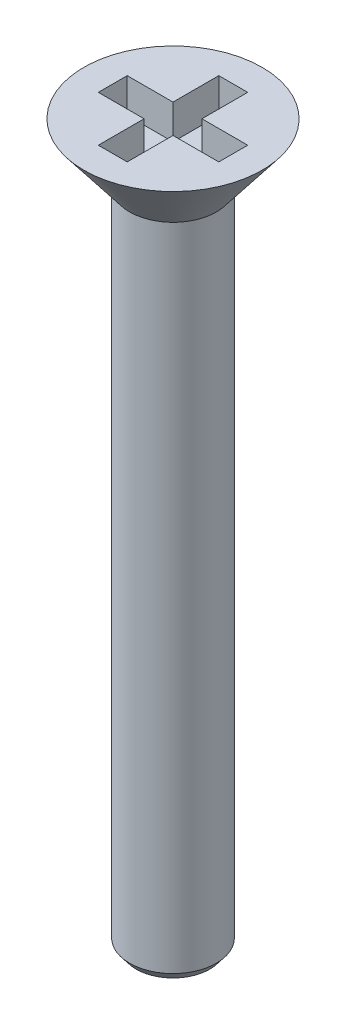
SolidWorks part; units mm, degrees
material "AISI 304"
ref_plane "Front Plane" through (0, 0, 0) normal (0, 0, 1) x (1, 0, 0)
ref_plane "Top Plane" through (0, 0, 0) normal (0, 1, 0) x (1, 0, 0)
ref_plane "Right Plane" through (0, 0, 0) normal (1, 0, 0) x (0, 0, -1)
sketch "Sketch1" plane through (0, 0, 0) normal (1, 0, 0) x (0, 0, -1)
  line L0 (0, 14.4405) -> (0, -19.6738) construction
  line L1 (0, 11.7897) -> (-3.7, 11.7897)
  line L2 (-3.7, 11.7897) -> (-1.8, 9.3397)
  line L3 (-1.8, 9.3397) -> (-1.8, -17.6603)
  line L4 (-1.8, -17.6603) -> (-1.5286, -18.0103)
  line L5 (-1.5286, -18.0103) -> (0, -18.0103)
  line L6 (0, 11.7897) -> (0, -18.0103)
  point P5 (0, 0)
  point P10 (0, -19.6738)
  dimension "D1" = 2.45
  dimension "D2" = 3.7
  dimension "D3" = 1.8
  dimension "D4" = 27
  dimension "D5" = 29.8
revolve "Revolve1" add sketch "Sketch1" angle 360 about L0
sketch "Sketch2" plane through (0, 11.7897, 0) normal (0, 1, 0) x (1, 0, 0)
  line L0 (0, 2.5) -> (0, -2.5) construction
  line L1 (2, 0) -> (-2, 0) construction
  line L2 (-2.5, -0.6) -> (-0.6, -0.6)
  line L3 (0.6, -2.5) -> (-0.6, -2.5)
  line L4 (0.6, -2.5) -> (0.6, -0.6)
  line L5 (0.6, 2.5) -> (-0.6, 2.5)
  line L6 (-0.6, -2.5) -> (-0.6, -0.6)
  line L7 (0.6, -2.5) -> (-0.6, 2.5) construction
  line L8 (0.6, 2.5) -> (-0.6, -2.5) construction
  line L9 (-2.5, -0.6) -> (-2.5, 0.6)
  line L10 (-2.5, 0.6) -> (-0.6, 0.6)
  line L11 (2.5, -0.6) -> (2.5, 0.6)
  line L12 (-0.6, 2.5) -> (-0.6, 0.6)
  line L13 (-0.6, 2.5) -> (0.6, 2.5)
  line L14 (0.6, 2.5) -> (0.6, 0.6)
  line L15 (-0.6, -2.5) -> (0.6, -2.5)
  line L16 (2.5, 0.6) -> (0.6, 0.6)
  line L17 (2.5, 0.6) -> (2.5, -0.6)
  line L18 (2.5, -0.6) -> (0.6, -0.6)
  line L19 (-2.5, 0.6) -> (-2.5, -0.6)
  line L20 (-0.6, 0.6) -> (-2.5, 0.6)
  line L22 (-0.6, -0.6) -> (-0.6, -2.5)
  line L23 (-0.6, 0.6) -> (-0.6, 2.5)
  line L24 (-0.6, -0.6) -> (-2.5, -0.6)
  line L26 (0.6, 0.6) -> (0.6, 2.5)
  line L27 (0.6, -0.6) -> (0.6, -2.5)
  line L28 (0.6, -0.6) -> (2.5, -0.6)
  line L30 (0.6, 0.6) -> (2.5, 0.6)
  point P3 (0, 0)
  point P6 (0, 0)
  point P7 (0, 0)
  point P27 (0, 0)
  dimension "D1" = 2
  dimension "D2" = 5
  dimension "D3" = 1.2
  dimension "D4" = 4
extrude "Cut-Extrude1" cut sketch "Sketch2" against normal blind 1.43 contours L18 L11 L16 L14 L5 L12 L10 L9 L2 L6 L3 L4
